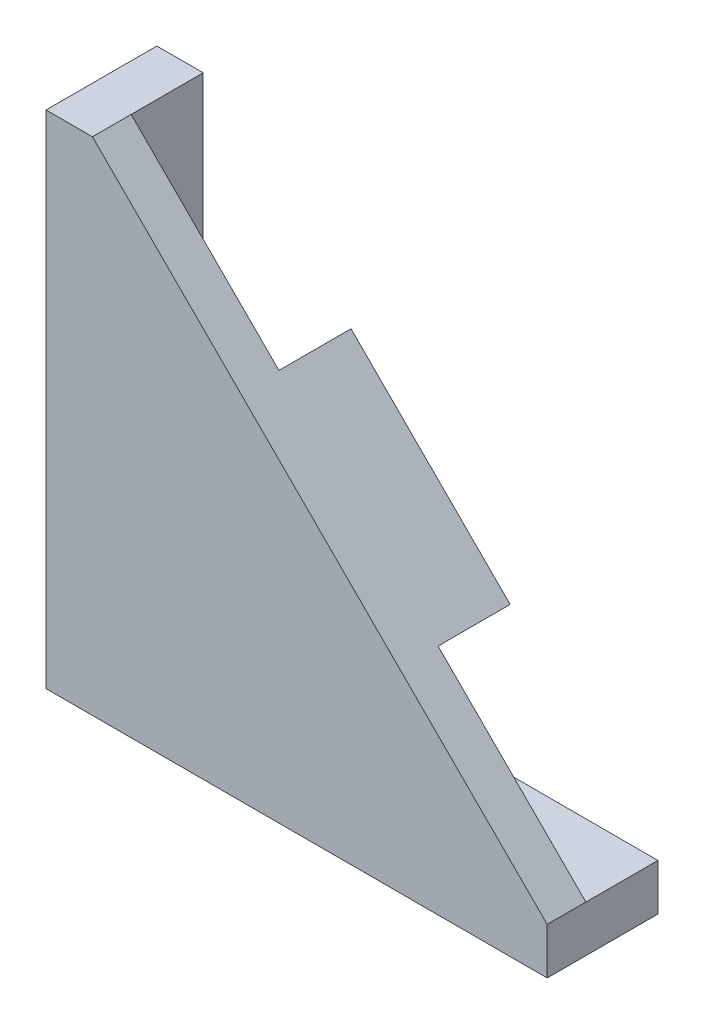
SolidWorks part; units mm, degrees
ref_plane "Front Plane" through (0, 0, 0) normal (0, 0, 1) x (1, 0, 0)
ref_plane "Top Plane" through (0, 0, 0) normal (0, 1, 0) x (1, 0, 0)
ref_plane "Right Plane" through (0, 0, 0) normal (1, 0, 0) x (0, 0, -1)
sketch "Sketch1" plane through (0, 0, 0) normal (0, 0, 1) x (1, 0, 0)
  line L0 (0, 0) -> (14.25, 0)
  line L1 (14.25, 0) -> (14.25, 1.32)
  line L2 (14.25, 1.32) -> (1.32, 14.25)
  line L3 (1.32, 14.25) -> (0, 14.25)
  line L4 (0, 14.25) -> (0, 0)
  dimension "D1" = 14.25
  dimension "D2" = 14.25
  dimension "D3" = 1.32
  dimension "D4" = 1.32
extrude "Boss-Extrude1" add sketch "Sketch1" against normal blind 3.15
sketch "Sketch2" plane through (0, 0, -3.15) normal (0, 0, -1) x (-1, 0, 0)
  line L0 (-14.25, 1.32) -> (-1.32, 1.32)
  line L1 (-1.32, 1.32) -> (-1.32, 14.25)
  line L6 (-14.25, 1.32) -> (-1.32, 14.25)
extrude "Cut-Extrude1" cut sketch "Sketch2" against normal blind 2.05
sketch "Sketch3" plane through (0, 0, -1.1) normal (0, 0, -1) x (-1, 0, 0)
  line L0 (-1.32, 14.25) -> (-14.25, 1.32) construction
  line L1 (-8.6594, 5.4964) -> (-5.4964, 8.6594)
  line L2 (-10.0477, 5.5223) -> (-5.5223, 10.0477)
  arc A0 (-8.6594, 5.4964) -> (-5.4964, 8.6594) centre (-7.785, 7.785) ccw
  arc A1 (-10.0477, 5.5223) -> (-5.5223, 10.0477) centre (-7.785, 7.785) ccw
  dimension "D1" = 3.2
  dimension "D2" = 2.45
  dimension "D3" = 1
extrude "Boss-Extrude2" add sketch "Sketch3" along normal up to surface (2.05 mm away) up to face at (5.19, 5.19, -3.15)
